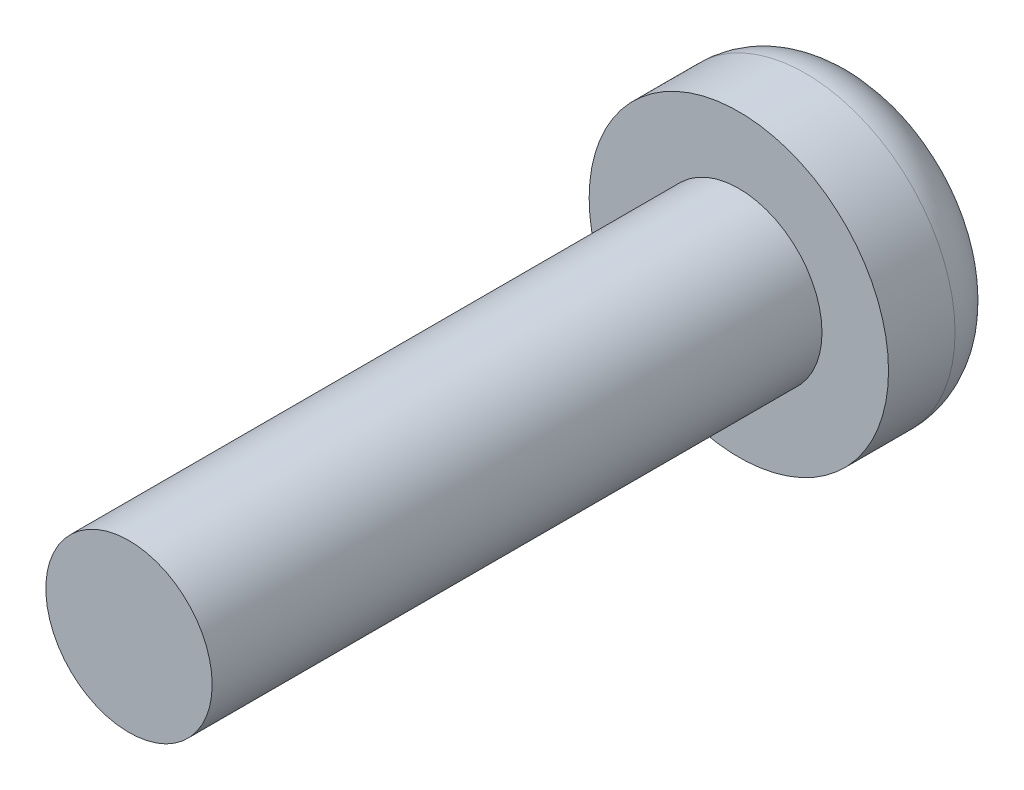
SolidWorks part; units mm, degrees
ref_plane "前视基准面" through (0, 0, 0) normal (0, 0, 1) x (1, 0, 0)
ref_plane "上视基准面" through (0, 0, 0) normal (0, 1, 0) x (1, 0, 0)
ref_plane "右视基准面" through (0, 0, 0) normal (1, 0, 0) x (0, 0, -1)
sketch "草图1" plane through (0, 0, 0) normal (0, 0, 1) x (1, 0, 0)
  circle A0 centre (0, 0) radius 1.5
extrude "凸台-拉伸1" add sketch "草图1" along normal blind 11
sketch "草图2" plane through (0, 0, 0) normal (0, 0, -1) x (-1, 0, 0)
  circle A0 centre (0, 0) radius 2.7
extrude "凸台-拉伸2" add sketch "草图2" along normal blind 2.2
fillet "圆角1" radius 1 1 edges at (-2.7, 0, -2.2)
